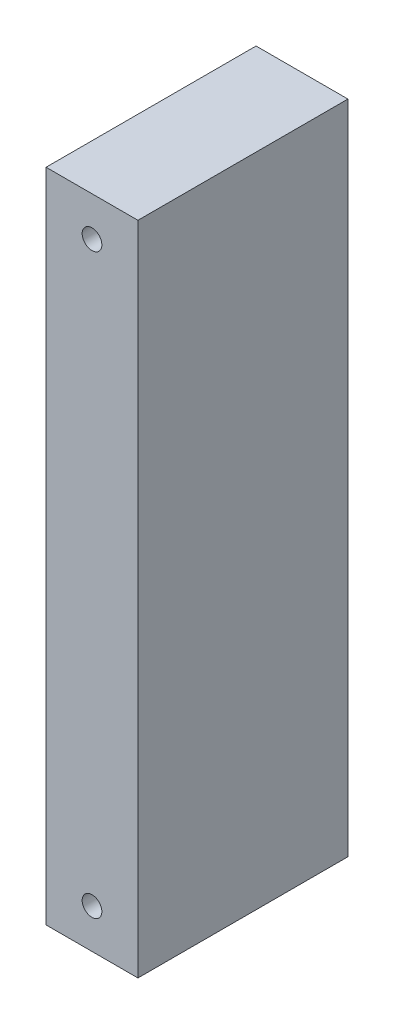
SolidWorks part; units mm, degrees
ref_plane "Front Plane" through (0, 0, 0) normal (0, 0, 1) x (1, 0, 0)
ref_plane "Top Plane" through (0, 0, 0) normal (0, 1, 0) x (1, 0, 0)
ref_plane "Right Plane" through (0, 0, 0) normal (1, 0, 0) x (0, 0, -1)
sketch "Sketch1" plane through (0, 0, 0) normal (0, 0, 1) x (1, 0, 0)
  line L1 (-3.5, -25) -> (3.5, -25)
  line L2 (-3.5, -25) -> (-3.5, 25)
  line L3 (-3.5, 25) -> (3.5, 25)
  line L4 (3.5, -25) -> (3.5, 25)
  line L5 (-3.5, -25) -> (3.5, 25) construction
  line L6 (-3.5, 25) -> (3.5, -25) construction
  circle A0 centre (0, 22) radius 0.75
  circle A1 centre (0, -22) radius 0.75
  point P0 (0, 0)
  dimension "D5" = 1.5
  dimension "D6" = 1.5
  dimension "D1" = 50
  dimension "D2" = 7
  dimension "D3" = 3
  dimension "D4" = 3
extrude "Boss-Extrude1" add sketch "Sketch1" along normal blind 14
sketch "Sketch3" plane through (0, 0, 0) normal (0, 0, -1) x (-1, 0, 0)
  line L1 (-3.5, 25) -> (3.5, 25)
  line L2 (-3.5, 25) -> (-3.5, -25)
  line L3 (-3.5, -25) -> (3.5, -25)
  line L4 (3.5, 25) -> (3.5, -25)
  circle A0 centre (0, 22) radius 0.75
  circle A1 centre (0, -22) radius 0.75
extrude "Boss-Extrude2" add sketch "Sketch3" along normal blind 2
sketch "Sketch4" plane through (0, 0, -2) normal (0, 0, -1) x (-1, 0, 0)
  circle A0 centre (0, 22) radius 0.75
